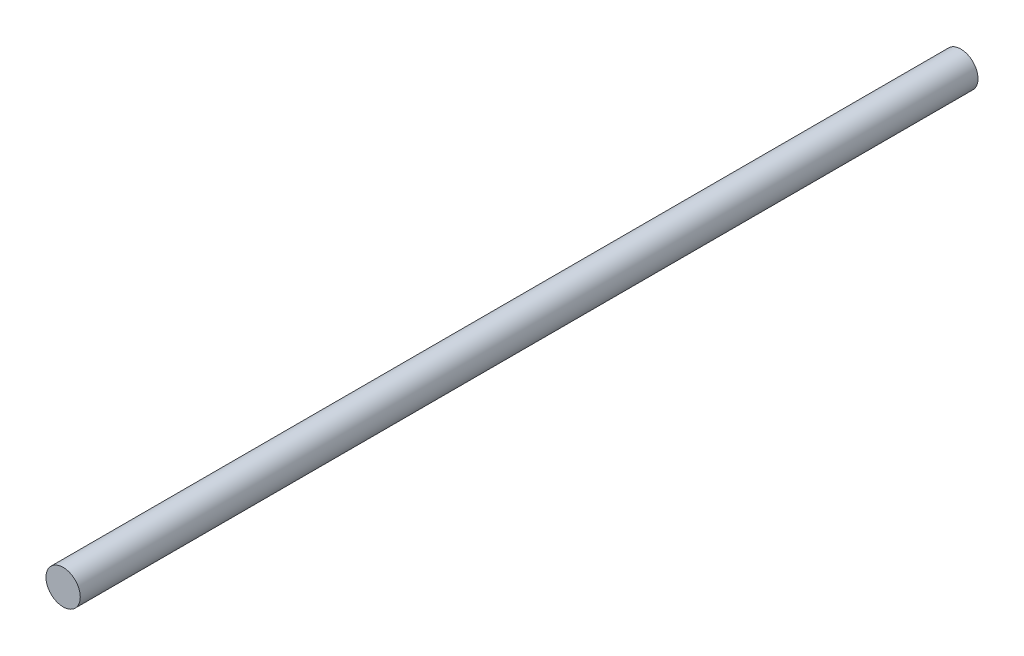
SolidWorks part; units mm, degrees
ref_plane "前视基准面" through (0, 0, 0) normal (0, 0, 1) x (1, 0, 0)
ref_plane "上视基准面" through (0, 0, 0) normal (0, 1, 0) x (1, 0, 0)
ref_plane "右视基准面" through (0, 0, 0) normal (1, 0, 0) x (0, 0, -1)
other "Configuration Table"
sketch "草图1" plane through (0, 0, 0) normal (0, 0, 1) x (1, 0, 0)
  circle A0 centre (0, 0) radius 3
  dimension "D1" = 6
extrude "凸台-拉伸1" add sketch "草图1" along normal blind 157
